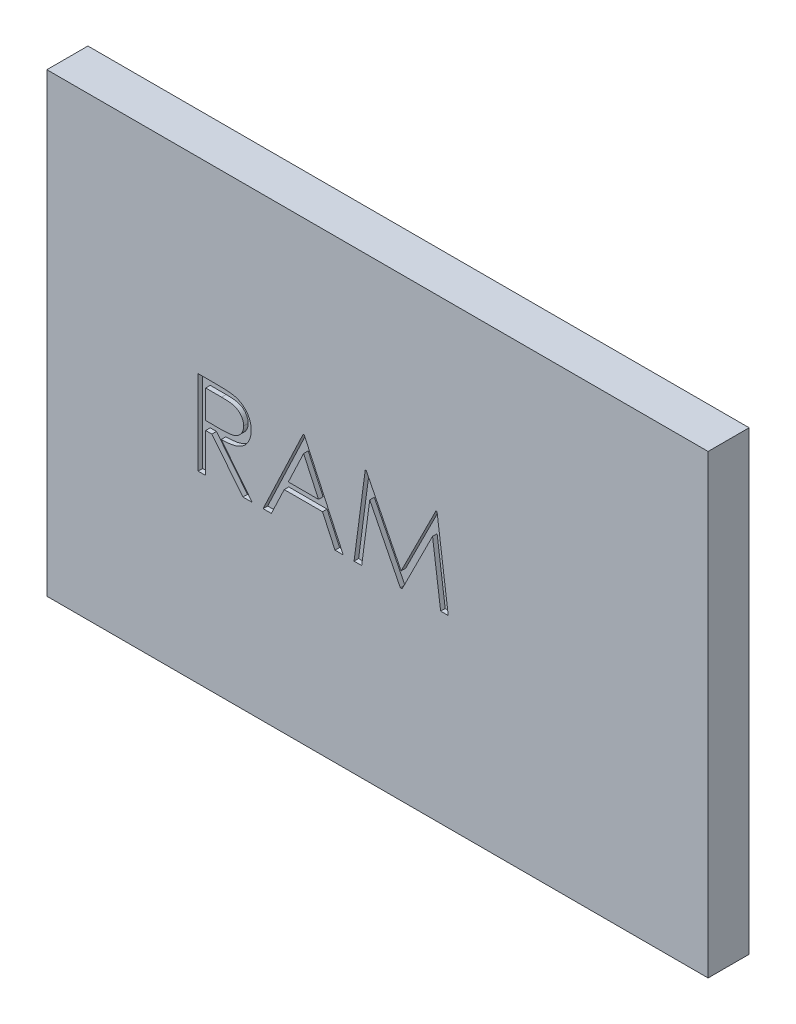
SolidWorks part; units mm, degrees
ref_plane "Front" through (0, 0, 0) normal (0, 0, 1) x (1, 0, 0)
ref_plane "Top" through (0, 0, 0) normal (0, 1, 0) x (1, 0, 0)
ref_plane "Right" through (0, 0, 0) normal (1, 0, 0) x (0, 0, -1)
sketch "Esquisse1" plane through (0, 0, 0) normal (0, 0, 1) x (1, 0, 0)
  line L1 (-7.25, -5) -> (7.25, -5)
  line L2 (-7.25, -5) -> (-7.25, 5)
  line L3 (-7.25, 5) -> (7.25, 5)
  line L4 (7.25, -5) -> (7.25, 5)
  line L5 (-7.25, -5) -> (7.25, 5) construction
  line L6 (-7.25, 5) -> (7.25, -5) construction
  point P0 (0, 0)
  dimension "D1" = 14.5
  dimension "D2" = 10
extrude "Boss.-Extru.1" add sketch "Esquisse1" along normal blind 0.9
sketch "Esquisse2" plane through (0, 0, 0.9) normal (0, 0, 1) x (1, 0, 0)
  text T0 "RAM" font "Century Gothic" height in points 7
extrude "Enlèv. mat.-Extru.1" cut sketch "Esquisse2" against normal blind 0.1
